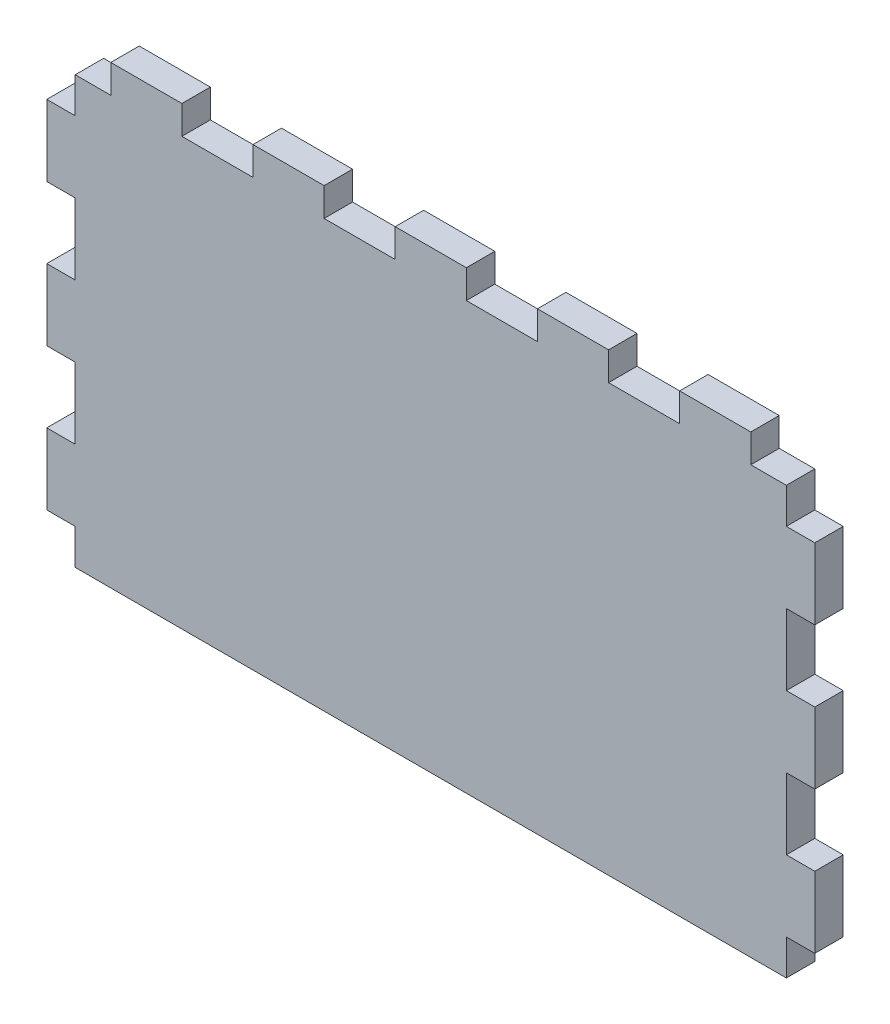
SolidWorks part; units mm, degrees
ref_plane "Front Plane" through (0, 0, 0) normal (0, 0, 1) x (1, 0, 0)
ref_plane "Top Plane" through (0, 0, 0) normal (0, 1, 0) x (1, 0, 0)
ref_plane "Right Plane" through (0, 0, 0) normal (1, 0, 0) x (0, 0, -1)
sketch "Sketch1" plane through (0, 0, 0) normal (0, 0, 1) x (1, 0, 0)
  line L0 (-50, 30) -> (-30, 30)
  line L1 (-50, -30) -> (50, -30)
  line L2 (-50, -30) -> (-50, 30)
  line L3 (-50, 30) -> (50, 30)
  line L4 (50, -30) -> (50, 30)
  line L5 (0, 30) -> (0, -30) construction
  line L6 (-50, 0) -> (50, 0) construction
  line L7 (-30, 30) -> (-10, 30)
  line L8 (-10, 30) -> (10, 30)
  line L9 (10, 30) -> (30, 30)
  line L10 (50, -30) -> (50, -10)
  line L11 (50, -10) -> (50, 10)
  line L12 (-50, -30) -> (-50, -10)
  line L13 (-45, 26) -> (-35, 26)
  line L14 (-45, 26) -> (-45, 34)
  line L15 (-45, 34) -> (-35, 34)
  line L16 (-35, 26) -> (-35, 34)
  line L17 (-40, 34) -> (-40, 26) construction
  line L18 (-45, 30) -> (-35, 30) construction
  line L19 (-25, 26) -> (-15, 26)
  line L20 (-25, 26) -> (-25, 34)
  line L21 (-25, 34) -> (-15, 34)
  line L22 (-15, 26) -> (-15, 34)
  line L23 (-20, 34) -> (-20, 26) construction
  line L24 (-25, 30) -> (-15, 30) construction
  line L25 (-5, 26) -> (5, 26)
  line L26 (-5, 26) -> (-5, 34)
  line L27 (-5, 34) -> (5, 34)
  line L28 (5, 26) -> (5, 34)
  line L29 (0, 34) -> (0, 26) construction
  line L30 (-5, 30) -> (5, 30) construction
  line L31 (15, 26) -> (25, 26)
  line L32 (15, 26) -> (15, 34)
  line L33 (15, 34) -> (25, 34)
  line L34 (25, 26) -> (25, 34)
  line L35 (20, 34) -> (20, 26) construction
  line L36 (15, 30) -> (25, 30) construction
  line L37 (35, 26) -> (45, 26)
  line L38 (35, 26) -> (35, 34)
  line L39 (35, 34) -> (45, 34)
  line L40 (45, 26) -> (45, 34)
  line L41 (40, 34) -> (40, 26) construction
  line L42 (35, 30) -> (45, 30) construction
  line L43 (46, 25) -> (54, 25)
  line L44 (46, 25) -> (46, 15)
  line L45 (46, 15) -> (54, 15)
  line L46 (54, 25) -> (54, 15)
  line L47 (50, 15) -> (50, 25) construction
  line L48 (46, 20) -> (54, 20) construction
  line L49 (46, 5) -> (54, 5)
  line L50 (46, 5) -> (46, -5)
  line L51 (46, -5) -> (54, -5)
  line L52 (54, 5) -> (54, -5)
  line L53 (50, -5) -> (50, 5) construction
  line L54 (46, 0) -> (54, 0) construction
  line L55 (46, -15) -> (54, -15)
  line L56 (46, -15) -> (46, -25)
  line L57 (46, -25) -> (54, -25)
  line L58 (54, -15) -> (54, -25)
  line L59 (50, -25) -> (50, -15) construction
  line L60 (46, -20) -> (54, -20) construction
  line L61 (-50, -10) -> (-50, 10)
  line L63 (-54, 25) -> (-46, 25)
  line L64 (-54, 25) -> (-54, 15)
  line L65 (-54, 15) -> (-46, 15)
  line L66 (-46, 25) -> (-46, 15)
  line L67 (-50, 15) -> (-50, 25) construction
  line L68 (-54, 20) -> (-46, 20) construction
  line L69 (-54, 5) -> (-46, 5)
  line L70 (-54, 5) -> (-54, -5)
  line L71 (-54, -5) -> (-46, -5)
  line L72 (-46, 5) -> (-46, -5)
  line L73 (-50, -5) -> (-50, 5) construction
  line L74 (-54, 0) -> (-46, 0) construction
  line L75 (-54, -15) -> (-46, -15)
  line L76 (-54, -15) -> (-54, -25)
  line L77 (-54, -25) -> (-46, -25)
  line L78 (-46, -15) -> (-46, -25)
  line L79 (-50, -25) -> (-50, -15) construction
  line L80 (-54, -20) -> (-46, -20) construction
  point P0 (0, 0)
  point P4 (-40, 30)
  point P11 (-20, 30)
  point P12 (20, 30)
  point P13 (0, 30)
  point P14 (40, 30)
  point P15 (50, 20)
  point P16 (50, -20)
  point P17 (50, 0)
  point P18 (-40, 30)
  point P22 (-20, 30)
  point P29 (20, 30)
  point P33 (40, 30)
  point P37 (50, 20)
  point P44 (50, -20)
  point P48 (-50, -20)
  point P51 (-50, 0)
  point P52 (-50, 20)
  point P53 (-50, 20)
  point P65 (-50, -20)
  dimension "D1" = 60
  dimension "D2" = 100
  dimension "D3" = 20
  dimension "D4" = 20
  dimension "D5" = 20
  dimension "D6" = 20
  dimension "D7" = 20
  dimension "D8" = 20
  dimension "D9" = 20
  dimension "D10" = 20
  dimension "D11" = 10
  dimension "D12" = 10
  dimension "D13" = 10
  dimension "D14" = 10
  dimension "D15" = 10
  dimension "D16" = 10
  dimension "D17" = 10
  dimension "D18" = 10
  dimension "D19" = 20
  dimension "D20" = 10
  dimension "D21" = 20
  dimension "D22" = 10
  dimension "D23" = 20
  dimension "D24" = 10
  dimension "D25" = 8
  dimension "D26" = 8
  dimension "D27" = 8
  dimension "D28" = 8
  dimension "D29" = 8
  dimension "D30" = 8
  dimension "D31" = 8
  dimension "D32" = 8
  dimension "D33" = 8
  dimension "D34" = 8
  dimension "D35" = 8
  dimension "D36" = 10
  dimension "D37" = 10
  dimension "D38" = 10
  dimension "D39" = 10
  dimension "D40" = 10
  dimension "D41" = 10
  dimension "D42" = 10
  dimension "D43" = 10
  dimension "D44" = 10
  dimension "D45" = 10
  dimension "D46" = 10
extrude "Boss-Extrude1" add sketch "Sketch1" along normal blind 4 contours L75 L78 L77 L2 L1 L4 L57 L56 L55 L10 L51 L50 L49 L11 L45 L44 L43 L3 L40 L37 L38 L34 L31 L32 L28 L25 L26 L22 L19 L20 L0 L16 L13 L14 L63 L66 L65 L61 | L64 L65 L2 L63 | L66 L63 L2 L65 | L70 L71 L61 L69 | L72 L69 L61 L71 | L13 L16 L3 L14 | L3 L16 L15 L14 | L78 L75 L12 L77 | L76 L77 L12 L75 | L7 L22 L21 L20 | L19 L22 L7 L20 | L8 L28 L27 L26 | L25 L28 L8 L26 | L9 L34 L33 L32 | L31 L34 L9 L32 | L3 L40 L39 L38 | L37 L40 L3 L38 | L46 L43 L4 L45 | L44 L45 L4 L43 | L52 L49 L11 L51 | L50 L51 L11 L49 | L56 L57 L10 L55 | L58 L55 L10 L57
